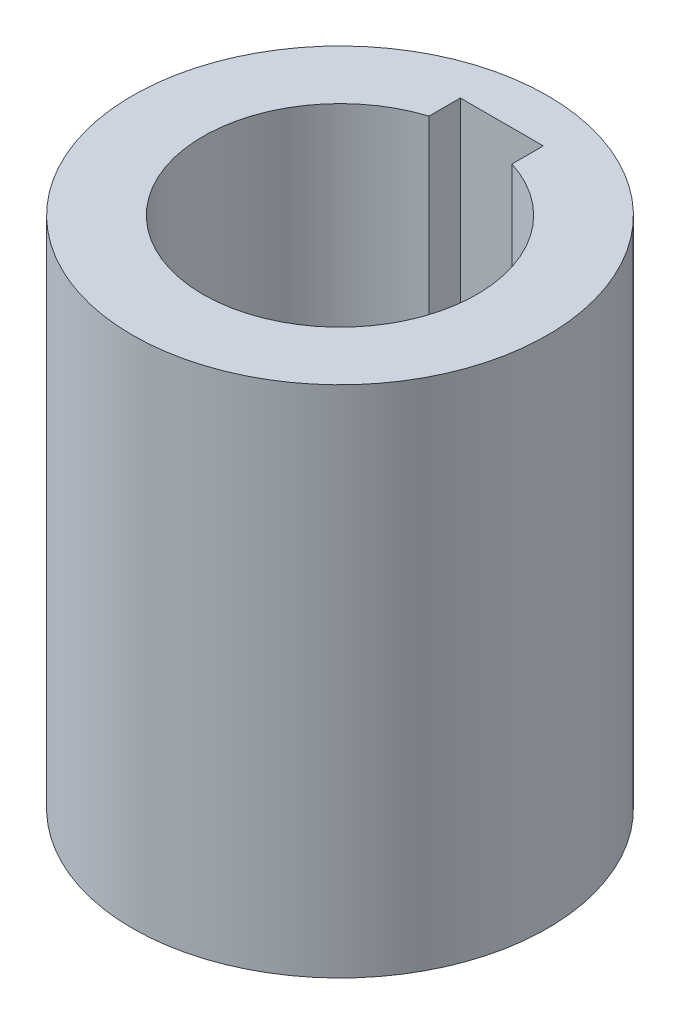
SolidWorks part; units mm, degrees
material "ASTM A36 Steel"
ref_plane "Front Plane" through (0, 0, 0) normal (0, 0, 1) x (1, 0, 0)
ref_plane "Top Plane" through (0, 0, 0) normal (0, 1, 0) x (1, 0, 0)
ref_plane "Right Plane" through (0, 0, 0) normal (1, 0, 0) x (0, 0, -1)
sketch "Sketch1" plane through (0, 0, 0) normal (0, 1, 0) x (1, 0, 0)
  circle A0 centre (0, 0) radius 50
  circle A1 centre (0, 0) radius 33
  dimension "D1" = 100
  dimension "D2" = 66
extrude "Boss-Extrude1" add sketch "Sketch1" along normal blind 123.8
sketch "Sketch2" plane through (0, 123.8, 0) normal (0, 1, 0) x (1, 0, 0)
  line L1 (-10, 27) -> (10, 27)
  line L2 (-10, 27) -> (-10, 39)
  line L3 (-10, 39) -> (10, 39)
  line L4 (10, 27) -> (10, 39)
  line L5 (-10, 27) -> (10, 39) construction
  line L6 (-10, 39) -> (10, 27) construction
  circle A0 centre (0, 0) radius 33 construction
  point P0 (0, 33)
  dimension "D1" = 20
  dimension "D2" = 12
extrude "Cut-Extrude1" cut sketch "Sketch2" against normal through all both and the other way through all
